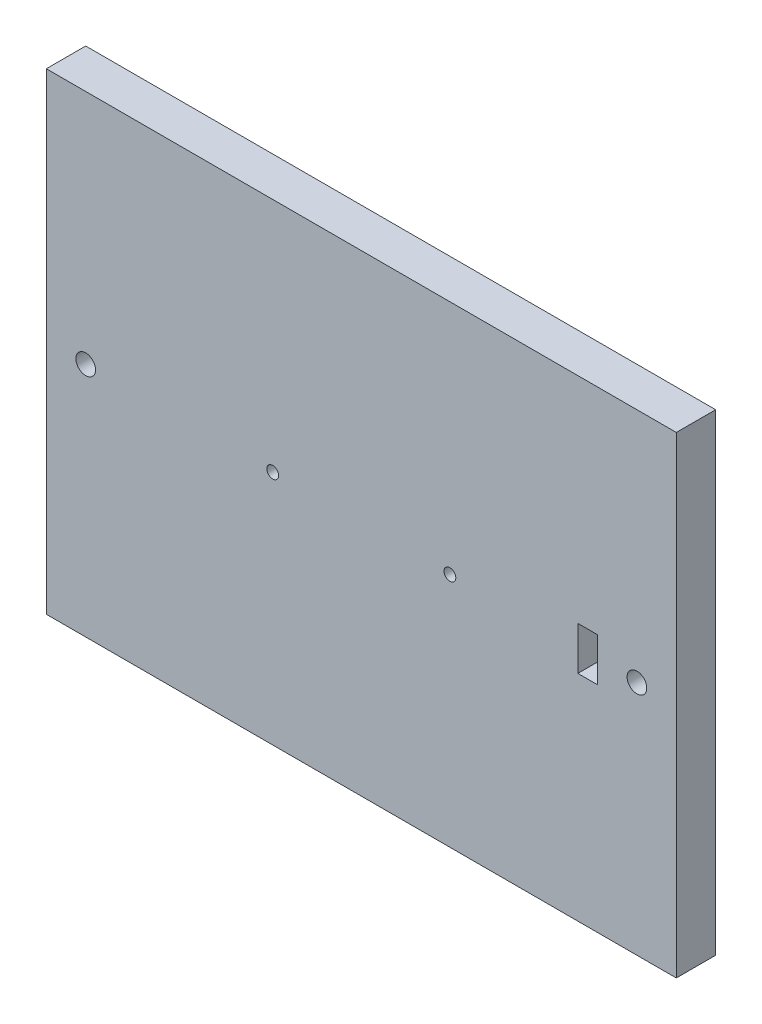
SolidWorks part; units mm, degrees
ref_plane "Front Plane" through (0, 0, 0) normal (0, 0, 1) x (1, 0, 0)
ref_plane "Top Plane" through (0, 0, 0) normal (0, 1, 0) x (1, 0, 0)
ref_plane "Right Plane" through (0, 0, 0) normal (1, 0, 0) x (0, 0, -1)
sketch "Sketch1" plane through (0, 0, 0) normal (0, 0, 1) x (1, 0, 0)
  line L0 (0, 0) -> (-22.5, 0) construction
  line L1 (-80, -60) -> (80, -60)
  line L2 (-80, -60) -> (-80, 60)
  line L3 (-80, 60) -> (80, 60)
  line L4 (80, -60) -> (80, 60)
  line L5 (-80, -60) -> (80, 60) construction
  line L6 (-80, 60) -> (80, -60) construction
  line L7 (0, 0) -> (22.5, 0) construction
  line L8 (-80, 0) -> (-70, 0) construction
  line L9 (80, 0) -> (70, 0) construction
  line L10 (-65, -5) -> (-75, -5)
  line L11 (-65, -5) -> (-65, 5)
  line L12 (-65, 5) -> (-75, 5)
  line L13 (-75, -5) -> (-75, 5)
  line L14 (-65, -5) -> (-75, 5) construction
  line L15 (-65, 5) -> (-75, -5) construction
  line L16 (0, 0) -> (0, -12.5) construction
  line L17 (75, -5) -> (65, -5)
  line L18 (75, -5) -> (75, 5)
  line L19 (75, 5) -> (65, 5)
  line L20 (65, -5) -> (65, 5)
  line L21 (75, -5) -> (65, 5) construction
  line L22 (75, 5) -> (65, -5) construction
  line L24 (45, -14) -> (-45, -14)
  line L25 (45, -14) -> (45, -11)
  line L26 (45, -11) -> (-45, -11)
  line L27 (-45, -14) -> (-45, -11)
  line L28 (45, -14) -> (-45, -11) construction
  line L29 (45, -11) -> (-45, -14) construction
  circle A0 centre (-22.5, 0) radius 1.5
  circle A1 centre (22.5, 0) radius 1.5
  circle A2 centre (-70, 0) radius 2.5
  circle A3 centre (70, 0) radius 2.5
  point P0 (0, 0)
  dimension "D4" = 3
  dimension "D6" = 3
  dimension "D8" = 5
  dimension "D12" = 5
  dimension "D1" = 160
  dimension "D2" = 120
  dimension "D3" = 22.5
  dimension "D5" = 22.5
  dimension "D7" = 10
  dimension "D9" = 10
  dimension "D10" = 10
  dimension "D11" = 10
  dimension "D13" = 10
  dimension "D14" = 10
  dimension "D15" = 12.5
  dimension "D16" = 3
  dimension "D17" = 90
extrude "Boss-Extrude1" add sketch "Sketch1" along normal blind 10 contours L4 L3 L2 L1
sketch "Sketch2" plane through (0, 0, 0) normal (0, 0, -1) x (-1, 0, 0)
  line L0 (-22.5, 0) -> (-57.5, 0) construction
  line L2 (-55, -5.5) -> (-60, -5.5)
  line L3 (-55, -5.5) -> (-55, 5.5)
  line L4 (-55, 5.5) -> (-60, 5.5)
  line L5 (-60, -5.5) -> (-60, 5.5)
  line L6 (-55, -5.5) -> (-60, 5.5) construction
  line L7 (-55, 5.5) -> (-60, -5.5) construction
  circle A0 centre (-22.5, 0) radius 1.5
  circle A1 centre (22.5, 0) radius 1.5
  circle A2 centre (70, 0) radius 2.5
  circle A3 centre (-70, 0) radius 2.5
  dimension "D1" = 5
  dimension "D2" = 3
  dimension "D3" = 3
  dimension "D4" = 5
  dimension "D5" = 5
  dimension "D6" = 11
  dimension "D7" = 35
extrude "Cut-Extrude2" cut sketch "Sketch2" against normal through all
sketch "Sketch3" plane through (0, 0, 0) normal (0, 0, -1) x (-1, 0, 0)
  line L1 (-65, -5) -> (-75, -5)
  line L2 (-65, -5) -> (-65, 5)
  line L3 (-65, 5) -> (-75, 5)
  line L4 (-75, -5) -> (-75, 5)
  line L5 (-65, -5) -> (-75, 5) construction
  line L6 (-65, 5) -> (-75, -5) construction
  line L7 (75, -5) -> (65, -5)
  line L8 (75, -5) -> (75, 5)
  line L9 (75, 5) -> (65, 5)
  line L10 (65, -5) -> (65, 5)
  line L11 (75, -5) -> (65, 5) construction
  line L12 (75, 5) -> (65, -5) construction
  point P0 (-70, 0)
  point P7 (70, 0)
extrude "Cut-Extrude3" cut sketch "Sketch3" against normal blind 4
sketch "Sketch4" plane through (0, 0, 0) normal (0, 0, -1) x (-1, 0, 0)
  line L1 (45, -14) -> (-45, -14)
  line L2 (45, -14) -> (45, -11)
  line L3 (45, -11) -> (-45, -11)
  line L4 (-45, -14) -> (-45, -11)
  line L5 (45, -14) -> (-45, -11) construction
  line L6 (45, -11) -> (-45, -14) construction
  point P0 (0, -12.5)
extrude "Boss-Extrude3" add sketch "Sketch4" along normal blind 25.05
sketch "Sketch5" plane through (0, -14, 0) normal (0, -1, 0) x (1, 0, 0)
  line L0 (0, 0) -> (0, -5.725) construction
  line L2 (0, -19.325) -> (0, -25.05) construction
  line L4 (3.2, -19.325) -> (3.2, -5.725)
  line L6 (-3.2, -19.325) -> (-3.2, -5.725)
  line L7 (45, -25.05) -> (-45, -25.05) construction
  arc A0 (3.2, -5.725) -> (-3.2, -5.725) centre (0, -5.725) ccw
  arc A2 (3.2, -19.325) -> (-3.2, -19.325) centre (0, -19.325) cw
  point P5 (0, -12.525)
  dimension "D3" = 6.4
  dimension "D4" = 6.4
  dimension "D5" = 3.2
  dimension "D1" = 5.725
  dimension "D2" = 13.6
  dimension "D6" = 5.725
extrude "Cut-Extrude5" cut sketch "Sketch5" against normal through all
